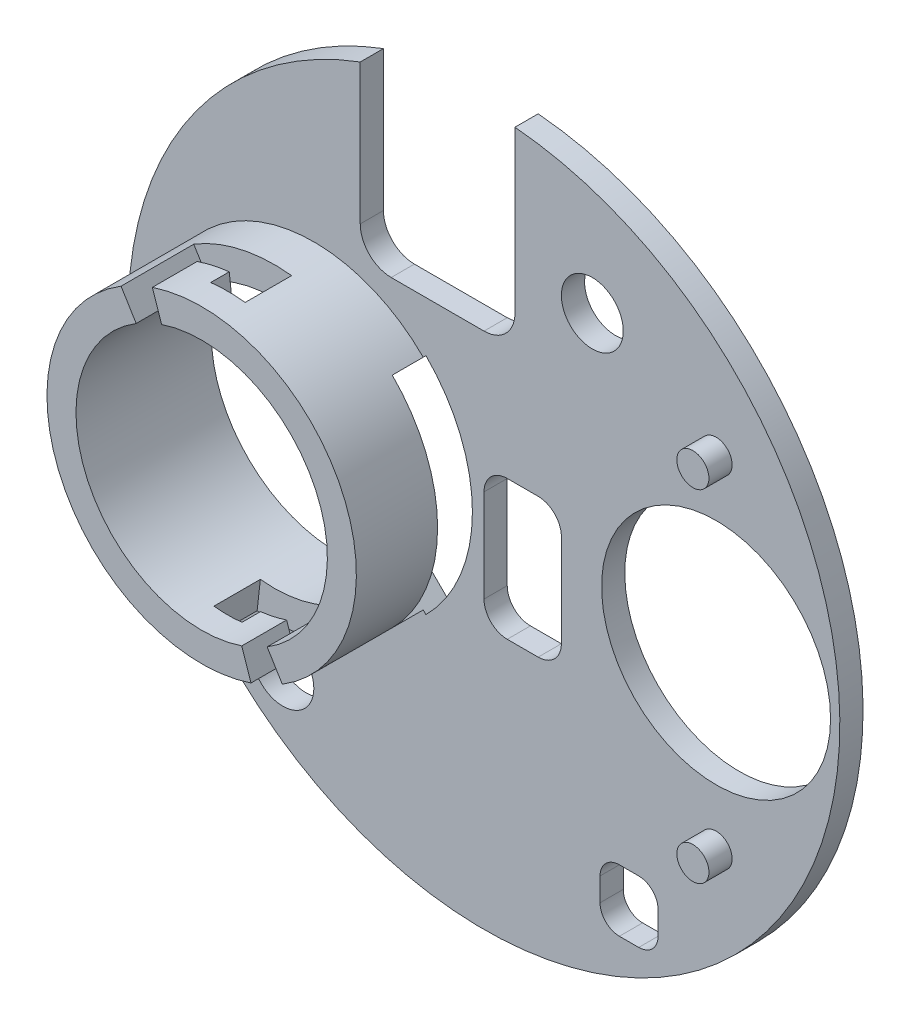
SolidWorks part; units mm, degrees
ref_plane "Front Plane" through (0, 0, 0) normal (0, 0, 1) x (1, 0, 0)
ref_plane "Top Plane" through (0, 0, 0) normal (0, 1, 0) x (1, 0, 0)
ref_plane "Right Plane" through (0, 0, 0) normal (1, 0, 0) x (0, 0, -1)
ref_plane "Plane_Z-19.50" through (0, 0, -19.5) normal (0, 0, 1) x (1, 0, 0)
sketch "Sketch1" plane through (0, 0, -19.5) normal (0, 0, 1) x (1, 0, 0)
  circle A0 centre (70, 0) radius 46
  dimension "CagePlateR" = 92
extrude "Cage_plate" add sketch "Sketch1" along normal blind 3
ref_plane "Plane_Z-16.50" through (0, 0, -16.5) normal (0, 0, 1) x (1, 0, 0)
sketch "Sketch2" plane through (0, 0, -16.5) normal (0, 0, 1) x (1, 0, 0)
  circle A0 centre (48, 0) radius 20
  circle A1 centre (48, 0) radius 16.25
  dimension "SocketOD" = 40
  dimension "SocketBore" = 32.5
extrude "Bayonet_socket" add sketch "Sketch2" along normal blind 14.5
sketch "Sketch3" plane through (0, 0, -16.5) normal (0, 0, 1) x (1, 0, 0)
  circle A0 centre (100, 22.05) radius 2.075
  circle A1 centre (100, -22.05) radius 2.075
extrude "Turbidity_ear_pins" add sketch "Sketch3" along normal blind 3
sketch "Sketch4" plane through (0, 0, -19.5) normal (0, 0, 1) x (1, 0, 0)
  circle A0 centre (48, 0) radius 16.25
  circle A1 centre (100, 0) radius 14.8
  dimension "TurbHeadBore" = 29.6
extrude "Hub_bore_and_turbidity_bore" cut sketch "Sketch4" against normal through all and the other way through all
sketch "Sketch5" plane through (0, 0, -19.5) normal (0, 0, 1) x (1, 0, 0)
  line L0 (58, 21) -> (70, 21)
  line L1 (74, 25) -> (74, 46)
  line L2 (70, 50) -> (58, 50)
  line L3 (54, 46) -> (54, 25)
  line L4 (87.5, -38) -> (90, -38)
  line L5 (92.5, -35.5) -> (92.5, -32.5)
  line L6 (90, -30) -> (87.5, -30)
  line L7 (85, -32.5) -> (85, -35.5)
  line L8 (73, -12) -> (77, -12)
  line L9 (80, -9) -> (80, 3)
  line L10 (77, 6) -> (73, 6)
  line L11 (70, 3) -> (70, -9)
  line L12 (20, -24) -> (32, -24)
  line L13 (32, -24) -> (32, -13)
  line L14 (32, -13) -> (20, -13)
  line L15 (20, -13) -> (20, -24)
  arc A0 (70, 21) -> (74, 25) centre (70, 25) ccw
  arc A1 (74, 46) -> (70, 50) centre (70, 46) ccw
  arc A2 (58, 50) -> (54, 46) centre (58, 46) ccw
  arc A3 (54, 25) -> (58, 21) centre (58, 25) ccw
  arc A4 (90, -38) -> (92.5, -35.5) centre (90, -35.5) ccw
  arc A5 (92.5, -32.5) -> (90, -30) centre (90, -32.5) ccw
  arc A6 (87.5, -30) -> (85, -32.5) centre (87.5, -32.5) ccw
  arc A7 (85, -35.5) -> (87.5, -38) centre (87.5, -35.5) ccw
  arc A8 (77, -12) -> (80, -9) centre (77, -9) ccw
  arc A9 (80, 3) -> (77, 6) centre (77, 3) ccw
  arc A10 (73, 6) -> (70, 3) centre (73, 3) ccw
  arc A11 (70, -9) -> (73, -12) centre (73, -9) ccw
  circle A12 centre (84, 30) radius 4
  circle A13 centre (44, -30) radius 4
extrude "TDS_notch_DS_hole_flow_window_hose_notch" cut sketch "Sketch5" against normal through all and the other way through all
ref_plane "Plane_Z-18.40" through (0, 0, -18.4) normal (0, 0, 1) x (1, 0, 0)
sketch "Sketch6" plane through (0, 0, -18.4) normal (0, 0, 1) x (1, 0, 0)
  circle A0 centre (30, 7) radius 2.15
  circle A1 centre (30, -7) radius 2.15
  circle A2 centre (106, 17) radius 2.15
  circle A3 centre (106, -17) radius 2.15
extrude "Post_pin_sockets_blind" cut sketch "Sketch6" against normal mid plane 3.2
ref_plane "Plane_Z-16.25" through (0, 0, -16.25) normal (0, 0, 1) x (1, 0, 0)
sketch "Sketch7" plane through (0, 0, -16.25) normal (0, 0, 1) x (1, 0, 0)
  line L0 (59.2076, -11.2076) -> (62.4957, -14.4957)
  line L1 (62.4957, 14.4957) -> (59.2076, 11.2076)
  arc A0 (62.4957, -14.4957) -> (62.4957, 14.4957) centre (48, 0) ccw
  arc A1 (59.2076, 11.2076) -> (59.2076, -11.2076) centre (48, 0) cw
extrude "Hub_cable_window" cut sketch "Sketch7" against normal mid plane 7.5
ref_plane "Plane_Z-6.45" through (0, 0, -6.45) normal (0, 0, 1) x (1, 0, 0)
sketch "Sketch8" plane through (0, 0, -6.45) normal (0, 0, 1) x (1, 0, 0)
  line L0 (42.9285, 15.0695) -> (41.4613, 19.4293)
  line L1 (37.3193, 17.4978) -> (39.7159, 13.5715)
  line L2 (53.0715, -15.0695) -> (54.5387, -19.4293)
  line L3 (58.6807, -17.4978) -> (56.2841, -13.5715)
  arc A0 (41.4613, 19.4293) -> (37.3193, 17.4978) centre (48, 0) ccw
  arc A1 (39.7159, 13.5715) -> (42.9285, 15.0695) centre (48, 0) cw
  arc A2 (54.5387, -19.4293) -> (58.6807, -17.4978) centre (48, 0) ccw
  arc A3 (56.2841, -13.5715) -> (53.0715, -15.0695) centre (48, 0) cw
extrude "J_entry_slots" cut sketch "Sketch8" against normal mid plane 9.9
ref_plane "Plane_Z-9.60" through (0, 0, -9.6) normal (0, 0, 1) x (1, 0, 0)
sketch "Sketch9" plane through (0, 0, -9.6) normal (0, 0, 1) x (1, 0, 0)
  line L0 (49.7724, 15.8009) -> (50.2851, 20.3722)
  line L1 (37.3193, 17.4978) -> (39.7159, 13.5715)
  line L2 (46.2276, -15.8009) -> (45.7149, -20.3722)
  line L3 (58.6807, -17.4978) -> (56.2841, -13.5715)
  arc A0 (50.2851, 20.3722) -> (37.3193, 17.4978) centre (48, 0) ccw
  arc A1 (39.7159, 13.5715) -> (49.7724, 15.8009) centre (48, 0) cw
  arc A2 (45.7149, -20.3722) -> (58.6807, -17.4978) centre (48, 0) ccw
  arc A3 (56.2841, -13.5715) -> (46.2276, -15.8009) centre (48, 0) cw
extrude "J_twist_channels" cut sketch "Sketch9" against normal mid plane 3.6
ref_plane "Plane_Z-8.40" through (0, 0, -8.4) normal (0, 0, 1) x (1, 0, 0)
sketch "Sketch10" plane through (0, 0, -8.4) normal (0, 0, 1) x (1, 0, 0)
  line L0 (49.7724, 15.8009) -> (50.2851, 20.3722)
  line L1 (45.7149, 20.3722) -> (46.2276, 15.8009)
  line L2 (46.2276, -15.8009) -> (45.7149, -20.3722)
  line L3 (50.2851, -20.3722) -> (49.7724, -15.8009)
  arc A0 (50.2851, 20.3722) -> (45.7149, 20.3722) centre (48, 0) ccw
  arc A1 (46.2276, 15.8009) -> (49.7724, 15.8009) centre (48, 0) cw
  arc A2 (45.7149, -20.3722) -> (50.2851, -20.3722) centre (48, 0) ccw
  arc A3 (49.7724, -15.8009) -> (46.2276, -15.8009) centre (48, 0) cw
extrude "J_lock_notches" cut sketch "Sketch10" against normal mid plane 6
